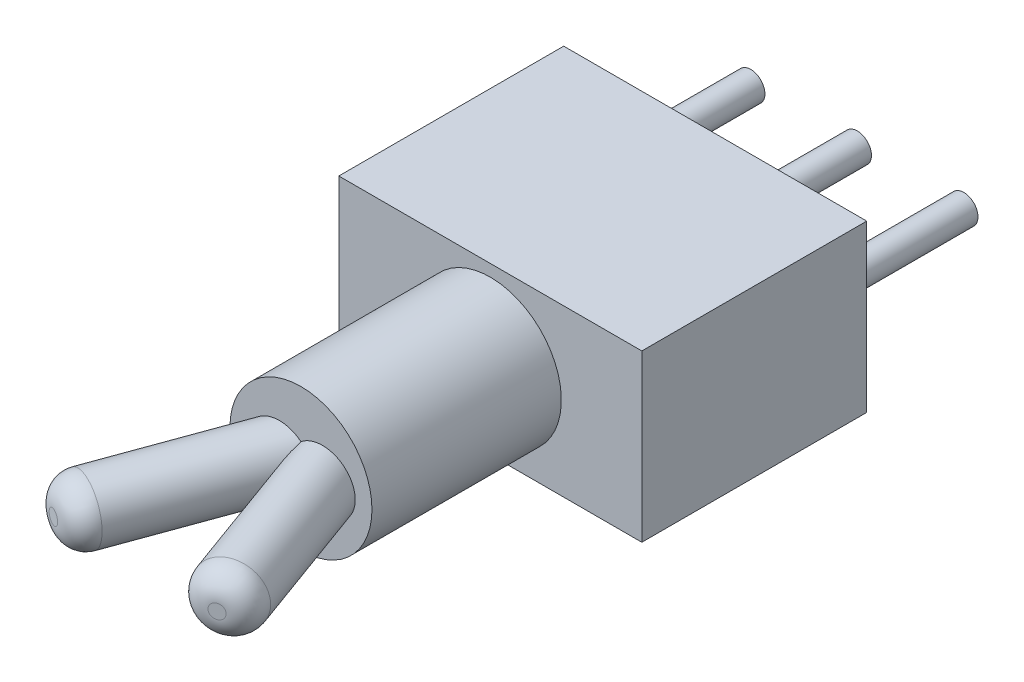
SolidWorks part; units mm, degrees
ref_plane "Front Plane" through (0, 0, 0) normal (0, 0, 1) x (1, 0, 0)
ref_plane "Top Plane" through (0, 0, 0) normal (0, 1, 0) x (1, 0, 0)
ref_plane "Right Plane" through (0, 0, 0) normal (1, 0, 0) x (0, 0, -1)
sketch "Sketch1" plane through (0, 0, 0) normal (0, 1, 0) x (1, 0, 0)
  line L1 (-6.4, 4.75) -> (6.4, 4.75)
  line L2 (-6.4, 4.75) -> (-6.4, -4.75)
  line L3 (-6.4, -4.75) -> (6.4, -4.75)
  line L4 (6.4, 4.75) -> (6.4, -4.75)
  line L5 (-6.4, 4.75) -> (6.4, -4.75) construction
  line L6 (-6.4, -4.75) -> (6.4, 4.75) construction
  point P0 (0, 0)
  dimension "D1" = 9.5
  dimension "D2" = 12.8
extrude "Boss-Extrude1" add sketch "Sketch1" along normal mid plane 7
sketch "Sketch2" plane through (0, 0, 4.75) normal (0, 0, 1) x (1, 0, 0)
  line L0 (6.4, 0) -> (-6.4, 0) construction
  line L1 (6.4, 3.5) -> (6.4, -3.5) construction
  line L2 (-6.4, 3.5) -> (-6.4, -3.5) construction
  circle A0 centre (0, 0) radius 3
  dimension "D1" = 6
extrude "Boss-Extrude2" add sketch "Sketch2" along normal blind 8
sketch "Sketch3" plane through (0, 0, 0) normal (0, 1, 0) x (1, 0, 0)
  line L0 (0, -10.25) -> (3.4577, -19.75) construction
  line L1 (0, 0) -> (0, -10.25) construction
  line L2 (-3, -12.75) -> (3, -12.75) construction
  dimension "D1" = 2.5
  dimension "D2" = 160
  dimension "D3" = 7
ref_plane "Plane1" through (3.4577, 0, 19.75) normal (0.342, 0, 0.9397) x (0.9397, 0, -0.342)
sketch "Sketch4" plane through (3.4577, 0, 19.75) normal (0.342, 0, 0.9397) x (0.9397, 0, -0.342)
  circle A0 centre (0, 0) radius 1.3
  dimension "D1" = 2.6
extrude "Boss-Extrude3" add sketch "Sketch4" against normal blind 10
fillet "Fillet1" radius 1 1 edges at (4.6793, 0, 19.3054)
mirror "Mirror1" about plane through (0, 0, 0) normal (1, 0, 0) of "Fillet1", "Boss-Extrude3"
sketch "Sketch5" plane through (0, 0, -4.75) normal (0, 0, -1) x (-1, 0, 0)
  line L0 (-4.5, 0) -> (0, 0) construction
  line L1 (0, 0) -> (4.5, 0) construction
  circle A0 centre (0, 0) radius 0.6
  circle A1 centre (-4.5, 0) radius 0.6
  circle A2 centre (4.5, 0) radius 0.6
  dimension "D1" = 1.2
  dimension "D2" = 4.5
extrude "Boss-Extrude4" add sketch "Sketch5" along normal blind 6
